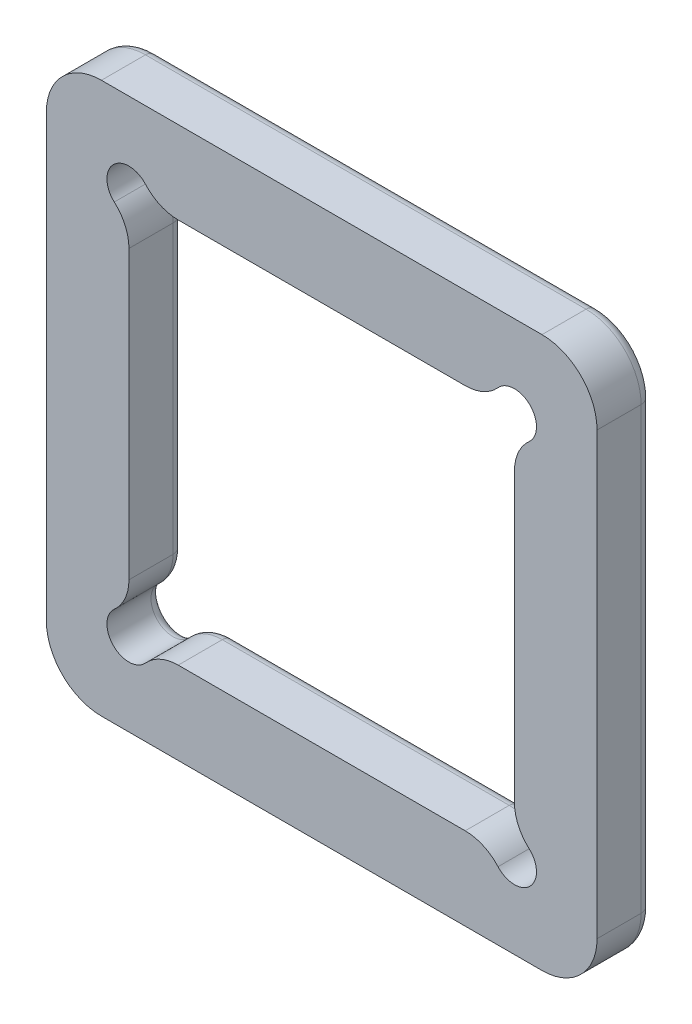
SolidWorks part; units mm, degrees
ref_plane "Alzado" through (0, 0, 0) normal (0, 0, 1) x (1, 0, 0)
ref_plane "Planta" through (0, 0, 0) normal (0, 1, 0) x (1, 0, 0)
ref_plane "Vista lateral" through (0, 0, 0) normal (1, 0, 0) x (0, 0, -1)
sketch "Croquis1" plane through (0, 0, 0) normal (0, 0, 1) x (1, 0, 0)
  line L1 (0, 0) -> (100, 0)
  line L2 (0, 0) -> (0, 100)
  line L3 (0, 100) -> (100, 100)
  line L4 (100, 0) -> (100, 100)
  line L5 (19, 15) -> (81, 15)
  line L6 (15, 19) -> (15, 81)
  line L7 (19, 85) -> (81, 85)
  line L8 (85, 19) -> (85, 81)
  arc A0 (19, 85) -> (15, 81) centre (15, 85) ccw
  arc A1 (85, 81) -> (81, 85) centre (85, 85) ccw
  arc A2 (81, 15) -> (85, 19) centre (85, 15) ccw
  arc A3 (15, 19) -> (19, 15) centre (15, 15) ccw
  point P13 (0, 0)
  point P15 (-1.0857, 0.4546)
  dimension "D1" = 8
  dimension "D2" = 8
  dimension "D3" = 8
  dimension "D4" = 8
  dimension "D5" = 70
  dimension "D6" = 70
  dimension "D7" = 100
  dimension "D8" = 100
  dimension "D9" = 15
  dimension "D10" = 15
extrude "Saliente-Extruir1" add sketch "Croquis1" along normal blind 10
fillet "Redondeo1" radius 8 8 edges at (85, 19, 5) (81, 15, 5) (15, 19, 5) (19, 15, 5) (15, 81, 5) (19, 85, 5) (81, 85, 5) (85, 81, 5)
fillet "Redondeo2" radius 10 4 edges at (100, 100, 5) (0, 100, 5) (0, 0, 5) (100, 0, 5)
fillet "Redondeo3" radius 2 24 edges at (79.3217, 14.303, 0) (50, 15, 0) (20.6783, 14.303, 0) (12.1716, 12.1716, 0) (14.303, 20.6783, 0) (15, 50, 0) (14.303, 79.3217, 0) (12.1716, 87.8284, 0) (20.6783, 85.697, 0) (50, 85, 0) (79.3217, 85.697, 0) (87.8284, 87.8284, 0) (85.697, 79.3217, 0) (85, 50, 0) (85.697, 20.6783, 0) (87.8284, 12.1716, 0) (2.9289, 97.0711, 0) (0, 50, 0) (2.9289, 2.9289, 0) (50, 0, 0) (97.0711, 2.9289, 0) (100, 50, 0) (97.0711, 97.0711, 0) (50, 100, 0)
sketch "Croquis2" plane through (0, 0, 0) normal (0, 0, -1) x (-1, 0, 0)
  line L0 (-23.9443, 13) -> (-76.0557, 13) construction
  line L1 (-25, 4) -> (-35, 4)
  line L2 (-25, 4) -> (-25, 11)
  line L3 (-25, 11) -> (-35, 11)
  line L4 (-35, 4) -> (-35, 11)
  line L5 (-45, 4) -> (-55, 4)
  line L6 (-45, 4) -> (-45, 11)
  line L7 (-45, 11) -> (-55, 11)
  line L8 (-55, 4) -> (-55, 11)
  line L9 (-65, 4) -> (-75, 4)
  line L10 (-65, 4) -> (-65, 11)
  line L11 (-65, 11) -> (-75, 11)
  line L12 (-75, 4) -> (-75, 11)
  line L13 (-89, 25) -> (-96, 25)
  line L14 (-89, 25) -> (-89, 35)
  line L15 (-89, 35) -> (-96, 35)
  line L16 (-96, 25) -> (-96, 35)
  line L17 (-89, 45) -> (-96, 45)
  line L18 (-89, 45) -> (-89, 55)
  line L19 (-89, 55) -> (-96, 55)
  line L20 (-96, 45) -> (-96, 55)
  line L21 (-89, 65) -> (-96, 65)
  line L22 (-89, 65) -> (-89, 75)
  line L23 (-89, 75) -> (-96, 75)
  line L24 (-96, 65) -> (-96, 75)
  line L25 (-4, 25) -> (-11, 25)
  line L26 (-4, 25) -> (-4, 35)
  line L27 (-4, 35) -> (-11, 35)
  line L28 (-11, 25) -> (-11, 35)
  line L29 (-4, 45) -> (-11, 45)
  line L30 (-4, 45) -> (-4, 55)
  line L31 (-4, 55) -> (-11, 55)
  line L32 (-11, 45) -> (-11, 55)
  line L33 (-4, 65) -> (-11, 65)
  line L34 (-4, 65) -> (-4, 75)
  line L35 (-4, 75) -> (-11, 75)
  line L36 (-11, 65) -> (-11, 75)
  line L37 (-25, 89) -> (-35, 89)
  line L38 (-25, 89) -> (-25, 96)
  line L39 (-25, 96) -> (-35, 96)
  line L40 (-35, 89) -> (-35, 96)
  line L41 (-45, 89) -> (-55, 89)
  line L42 (-45, 89) -> (-45, 96)
  line L43 (-45, 96) -> (-55, 96)
  line L44 (-55, 89) -> (-55, 96)
  line L45 (-65, 89) -> (-75, 89)
  line L46 (-65, 89) -> (-65, 96)
  line L47 (-65, 96) -> (-75, 96)
  line L48 (-75, 89) -> (-75, 96)
  line L50 (-100, 10) -> (-100, 90) construction
  line L51 (-10, 0) -> (-90, 0) construction
  line L52 (-13, 76.0557) -> (-13, 23.9443) construction
  line L53 (-76.0557, 87) -> (-23.9443, 87) construction
  line L54 (-87, 23.9443) -> (-87, 76.0557) construction
  dimension "D1" = 25
  dimension "D2" = 10
  dimension "D3" = 2
  dimension "D4" = 10
  dimension "D5" = 10
  dimension "D6" = 10
  dimension "D7" = 10
  dimension "D8" = 2
  dimension "D9" = 2
  dimension "D10" = 7
  dimension "D11" = 7
  dimension "D12" = 7
  dimension "D13" = 10
  dimension "D14" = 10
  dimension "D15" = 10
  dimension "D16" = 10
  dimension "D17" = 10
  dimension "D18" = 10
  dimension "D19" = 10
  dimension "D20" = 10
  dimension "D21" = 10
  dimension "D22" = 10
  dimension "D23" = 10
  dimension "D24" = 10
  dimension "D25" = 10
  dimension "D26" = 25
  dimension "D27" = 25
  dimension "D28" = 7
  dimension "D29" = 7
  dimension "D30" = 7
  dimension "D31" = 7
  dimension "D32" = 7
  dimension "D33" = 7
  dimension "D34" = 2
  dimension "D35" = 2
  dimension "D36" = 2
  dimension "D37" = 2
  dimension "D38" = 2
  dimension "D39" = 2
  dimension "D40" = 2
  dimension "D41" = 2
  dimension "D42" = 2
  dimension "D43" = 7
  dimension "D44" = 7
  dimension "D45" = 7
  dimension "D46" = 10
  dimension "D47" = 10
  dimension "D48" = 25
extrude "Cortar-Extruir1" cut sketch "Croquis2" against normal blind 7
